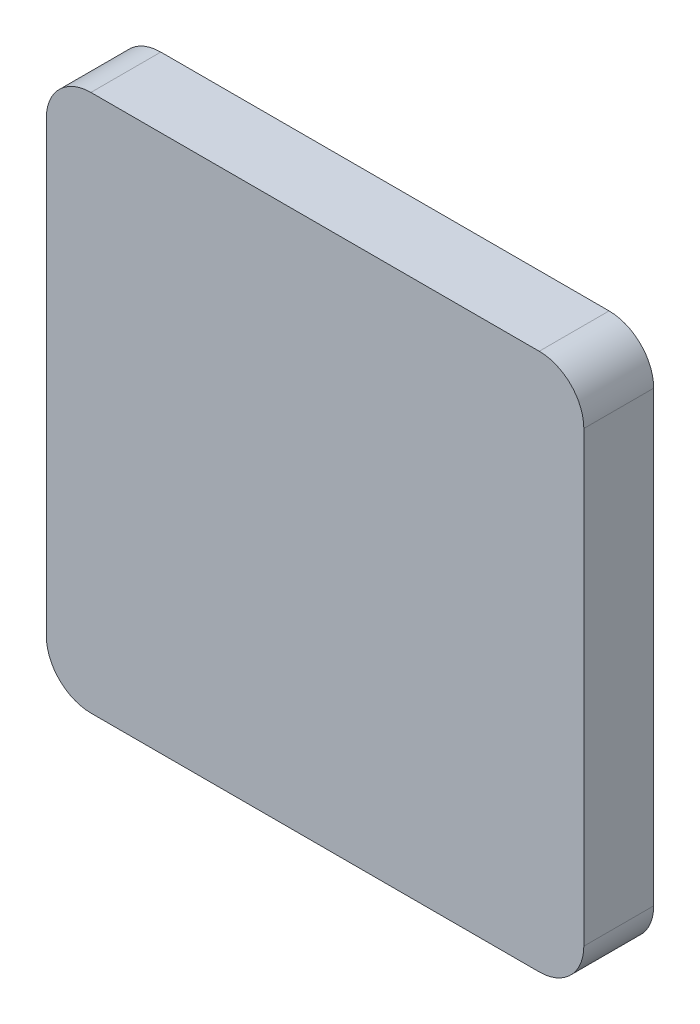
SolidWorks part; units mm, degrees
ref_plane "Front Plane" through (0, 0, 0) normal (0, 0, 1) x (1, 0, 0)
ref_plane "Top Plane" through (0, 0, 0) normal (0, 1, 0) x (1, 0, 0)
ref_plane "Right Plane" through (0, 0, 0) normal (1, 0, 0) x (0, 0, -1)
sketch "Sketch1" plane through (0, 0, 0) normal (0, 0, 1) x (-1, 0, 0)
  line L0 (10.5918, 12.7) -> (-10.5918, 12.7)
  line L1 (-12.7, 10.5918) -> (-12.7, -10.5918)
  line L2 (-10.5918, -12.7) -> (10.5918, -12.7)
  line L3 (12.7, -10.5918) -> (12.7, 10.5918)
  arc A0 (-10.5918, 12.7) -> (-12.7, 10.5918) centre (-10.5918, 10.5918) ccw
  arc A1 (-12.7, -10.5918) -> (-10.5918, -12.7) centre (-10.5918, -10.5918) ccw
  arc A2 (10.5918, -12.7) -> (12.7, -10.5918) centre (10.5918, -10.5918) ccw
  arc A3 (12.7, 10.5918) -> (10.5918, 12.7) centre (10.5918, 10.5918) ccw
extrude "Boss-Extrude1" add sketch "Sketch1" along normal blind 3.302
